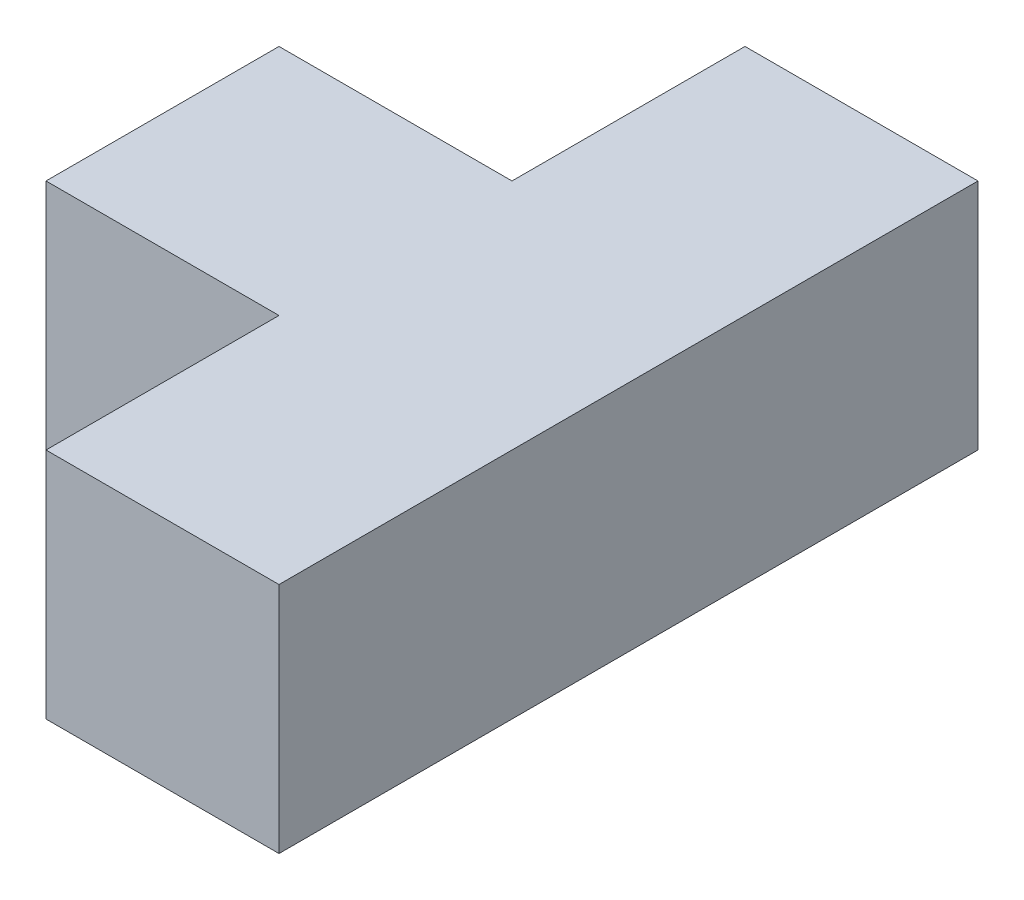
SolidWorks part; units mm, degrees
ref_plane "Front Plane" through (0, 0, 0) normal (0, 0, 1) x (1, 0, 0)
ref_plane "Top Plane" through (0, 0, 0) normal (0, 1, 0) x (1, 0, 0)
ref_plane "Right Plane" through (0, 0, 0) normal (1, 0, 0) x (0, 0, -1)
other "Center of Mass"
sketch "Sketch1" plane through (0, 0, 0) normal (0, 1, 0) x (1, 0, 0)
  line L0 (0, 0) -> (0, 30)
  line L1 (0, 30) -> (30, 30)
  line L2 (30, 30) -> (30, -60)
  line L3 (30, -60) -> (0, -60)
  line L4 (0, -60) -> (0, -30)
  line L5 (0, -30) -> (-30, -30)
  line L6 (-30, -30) -> (-30, 0)
  line L7 (-30, 0) -> (0, 0)
  dimension "D1" = 90
  dimension "D2" = 30
  dimension "D3" = 30
  dimension "D4" = 30
  dimension "D5" = 30
extrude "Boss-Extrude1" add sketch "Sketch1" along normal blind 30
